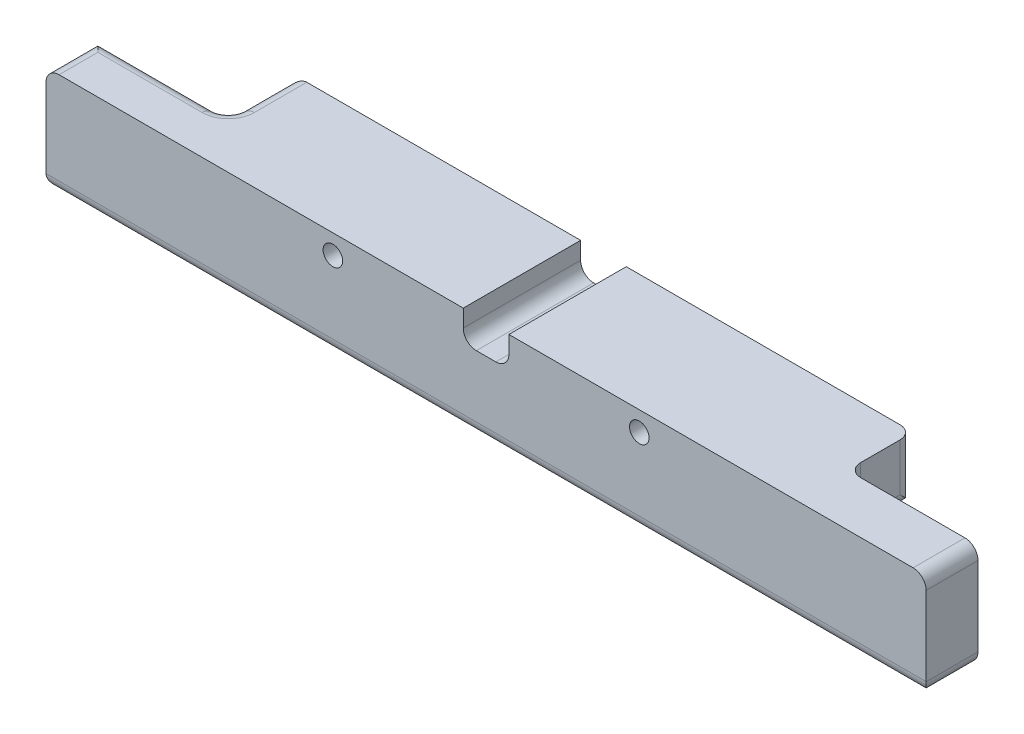
SolidWorks part; units mm, degrees
ref_plane "Plan de face" through (0, 0, 0) normal (0, 0, 1) x (1, 0, 0)
ref_plane "Plan de dessus" through (0, 0, 0) normal (0, 1, 0) x (1, 0, 0)
ref_plane "Plan de droite" through (0, 0, 0) normal (1, 0, 0) x (0, 0, -1)
sketch "Esquisse1" plane through (0, 0, 0) normal (0, 0, 1) x (1, 0, 0)
  line L0 (0, 4.5) -> (0, -18.0672) construction
  line L1 (-47.5, 4.65) -> (-3.5, 4.65)
  line L2 (-47.5, 4.65) -> (-47.5, -4.65)
  line L3 (-47.5, -4.65) -> (47.5, -4.65)
  line L4 (47.5, 4.65) -> (47.5, -4.65)
  line L5 (-47.5, 0) -> (65.9811, 0) construction
  line L6 (-3.5, 4.65) -> (-3.5, 0)
  line L7 (-3.5, 0) -> (3.5, 0)
  line L8 (3.5, 0) -> (3.5, 4.65)
  line L9 (3.5, 4.65) -> (47.5, 4.65)
  point P8 (0, 0)
  dimension "D1" = 9.3
  dimension "D2" = 95
  dimension "D3" = 7
extrude "Boss.-Extru.1" add sketch "Esquisse1" along normal blind 18
sketch "Esquisse2" plane through (0, 0, 18) normal (0, 0, 1) x (1, 0, 0)
  line L0 (0, 0) -> (0, -19.191) construction
  line L1 (-3.5, 4.65) -> (-47.5, 4.65) construction
  circle A0 centre (-23.5, 1.65) radius 1.5
  circle A1 centre (23.5, 1.65) radius 1.5
  dimension "D1" = 3
  dimension "D2" = 47
  dimension "D3" = 3
extrude "Enlèv. mat.-Extru.1" cut sketch "Esquisse2" against normal through all
sketch "Esquisse3" plane through (-47.5, 0, 0) normal (-1, 0, 0) x (0, 0, 1)
  line L1 (18, -4.65) -> (10.049, -4.65)
  line L2 (18, -4.65) -> (18, -11.4801)
  line L3 (18, -11.4801) -> (10.049, -11.4801)
  line L4 (10.049, -4.65) -> (10.049, -11.4801)
extrude "Boss.-Extru.2" add sketch "Esquisse3" against normal up to surface (95 mm away) up to face at (47.5, 0, 9)
sketch "Esquisse4" plane through (0, 0, 18) normal (0, 0, 1) x (1, 0, 0)
  line L0 (0, 0) -> (0, -26.0877) construction
  line L1 (47.5, -11.4801) -> (-47.5, -11.4801) construction
  line L2 (-47.5, 4.65) -> (-67.5, 4.65)
  line L3 (-47.5, 4.65) -> (-47.5, -11.4801)
  line L4 (-47.5, -11.4801) -> (-67.5, -11.4801)
  line L5 (-67.5, 4.65) -> (-67.5, -11.4801)
  line L6 (67.5, 4.65) -> (67.5, -11.4801)
  line L7 (47.5, -11.4801) -> (67.5, -11.4801)
  line L8 (47.5, 4.65) -> (47.5, -11.4801)
  line L9 (47.5, 4.65) -> (67.5, 4.65)
  dimension "D1" = 20
extrude "Boss.-Extru.3" add sketch "Esquisse4" against normal up to surface (7.951 mm away) up to face at (0, -8.0651, 10.049)
fillet "Congé1" radius 2 15 edges at (-47.5, 4.65, 5.0245) (0, -4.65, 10.049) (0, -11.4801, 18) (-3.5, 0, 9) (3.5, 0, 9) (-57.5, 4.65, 10.049) (47.5, -4.65, 5.0245) (47.5, 0, 0) (-47.5, 0, 0) (47.5, 0, 10.049) (-47.5, 0, 10.049) (67.5, 4.65, 14.0245) (67.5, -11.4801, 14.0245) (-67.5, 4.65, 14.0245) (-67.5, -11.4801, 14.0245)
